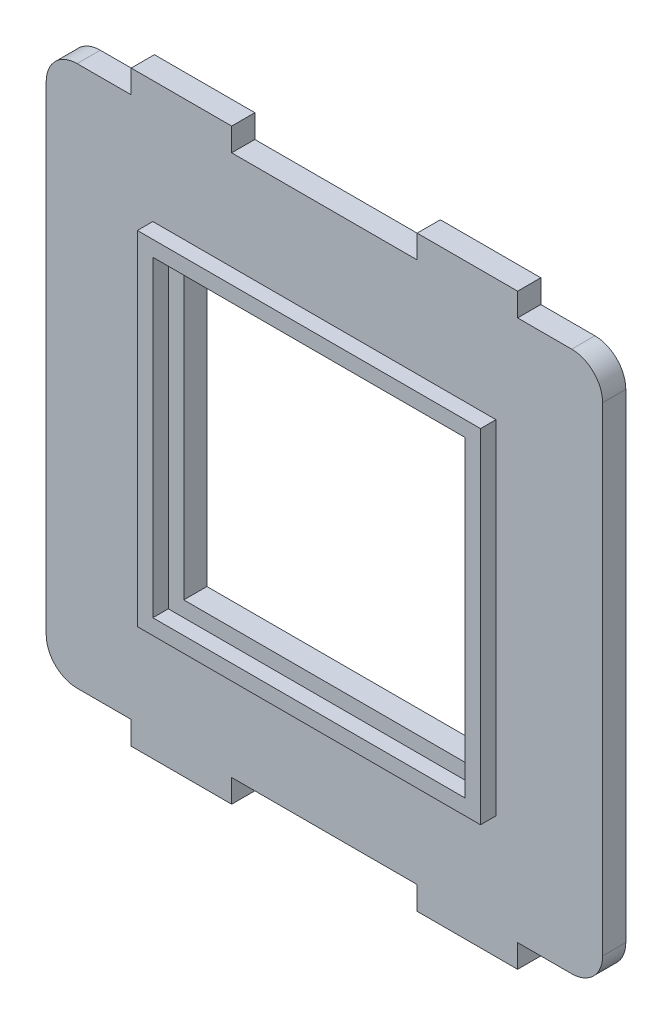
SolidWorks part; units mm, degrees
ref_plane "Front Plane" through (0, 0, 0) normal (0, 0, 1) x (1, 0, 0)
ref_plane "Top Plane" through (0, 0, 0) normal (0, 1, 0) x (1, 0, 0)
ref_plane "Right Plane" through (0, 0, 0) normal (1, 0, 0) x (0, 0, -1)
sketch "Sketch1" plane through (0, 0, 0) normal (0, 0, 1) x (1, 0, 0)
  line L0 (-18, 0) -> (18, 0) construction
  line L1 (-18, -17.5) -> (-12.5, -17.5)
  line L2 (-18, -17.5) -> (-18, 17.5)
  line L3 (-18, 17.5) -> (-12.5, 17.5)
  line L4 (18, -17.5) -> (18, 17.5)
  line L5 (-18, -17.5) -> (18, 17.5) construction
  line L6 (-18, 17.5) -> (18, -17.5) construction
  line L7 (12.5, 17.5) -> (18, 17.5)
  line L8 (-6, 17.5) -> (-6, 19)
  line L9 (-6, 19) -> (-12.5, 19)
  line L10 (-12.5, 17.5) -> (-12.5, 19)
  line L11 (12.5, -17.5) -> (18, -17.5)
  line L12 (6, 17.5) -> (6, 19)
  line L13 (6, 19) -> (12.5, 19)
  line L14 (12.5, 17.5) -> (12.5, 19)
  line L15 (12.5, -17.5) -> (12.5, -19)
  line L16 (6, -19) -> (12.5, -19)
  line L17 (6, -17.5) -> (6, -19)
  line L18 (-6, -17.5) -> (6, -17.5)
  line L19 (-12.5, -17.5) -> (-12.5, -19)
  line L20 (-6, -19) -> (-12.5, -19)
  line L21 (-6, -17.5) -> (-6, -19)
  line L23 (-6, 19) -> (6, 19) construction
  line L24 (0, 19) -> (0, 0) construction
  line L25 (-6, 17.5) -> (6, 17.5)
  point P0 (0, 0)
  dimension "D1" = 35
  dimension "D2" = 36
  dimension "D3" = 1.5
  dimension "D4" = 12
  dimension "D5" = 25
extrude "Boss-Extrude1" add sketch "Sketch1" along normal blind 1.5
sketch "Sketch2" plane through (0, 0, 1.5) normal (0, 0, 1) x (1, 0, 0)
  line L0 (-11.1, 11.1) -> (11.1, 11.1)
  line L1 (-10.1, -10.1) -> (10.1, -10.1)
  line L2 (-10.1, -10.1) -> (-10.1, 10.1)
  line L3 (-10.1, 10.1) -> (10.1, 10.1)
  line L4 (10.1, -10.1) -> (10.1, 10.1)
  line L5 (-10.1, -10.1) -> (10.1, 10.1) construction
  line L6 (-10.1, 10.1) -> (10.1, -10.1) construction
  line L7 (11.1, -11.1) -> (11.1, 11.1)
  line L8 (-11.1, -11.1) -> (11.1, -11.1)
  line L9 (-11.1, -11.1) -> (-11.1, 11.1)
  point P0 (0, 0)
  dimension "D1" = 20.2
  dimension "D2" = 1
extrude "Boss-Extrude2" add sketch "Sketch2" along normal blind 1
sketch "Sketch3" plane through (0, 0, 1.5) normal (0, 0, 1) x (1, 0, 0)
  line L0 (9.1, 9.1) -> (-9.1, 9.1)
  line L1 (-9.1, 9.1) -> (-9.1, -9.1)
  line L2 (-9.1, -9.1) -> (9.1, -9.1)
  line L3 (9.1, -9.1) -> (9.1, 9.1)
  line L4 (10.1, -10.1) -> (10.1, 10.1)
  line L5 (10.1, 10.1) -> (-10.1, 10.1)
  line L6 (-10.1, 10.1) -> (-10.1, -10.1)
  line L7 (-10.1, -10.1) -> (10.1, -10.1)
  line L8 (10.1, -10.1) -> (10.1, 10.1) construction
  line L9 (10.1, 10.1) -> (-10.1, 10.1) construction
  line L10 (-10.1, 10.1) -> (-10.1, -10.1) construction
  line L11 (-10.1, -10.1) -> (10.1, -10.1) construction
  dimension "D1" = 0
  dimension "D2" = 1
extrude "Cut-Extrude1" cut sketch "Sketch3" against normal through all
fillet "Fillet1" radius 2 4 edges at (-18, 17.5, 0.75) (18, 17.5, 0.75) (18, -17.5, 0.75) (-18, -17.5, 0.75)
